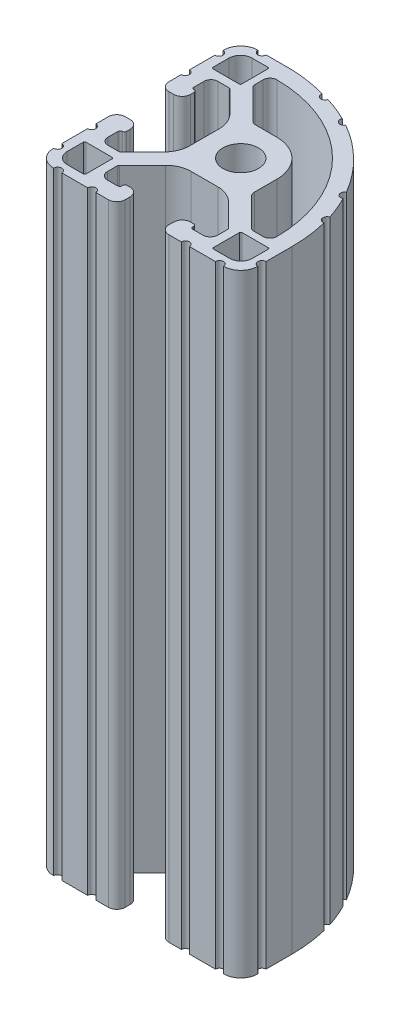
SolidWorks part; units mm, degrees
material "6061-T6 (SS)"
ref_plane "Front" through (0, 0, 0) normal (0, 0, 1) x (1, 0, 0)
ref_plane "Top" through (0, 0, 0) normal (0, 1, 0) x (1, 0, 0)
ref_plane "Right" through (0, 0, 0) normal (1, 0, 0) x (0, 0, -1)
sketch "Sketch1" plane through (0, 0, 0) normal (0, 0, 1) x (1, 0, 0)
  line L0 (0, -57.15) -> (0, 57.15)
  dimension "D1" = 114.3
other "15 1517 PROFILE(1)"
ref_plane "Plane1" through (0, -57.15, 0) normal (0, 1, 0) x (-1, 0, 0)
sketch "Sketch12" plane through (0, -57.15, 0) normal (0, 1, 0) x (-1, 0, 0)
  line L0 (0, 18.8774) -> (0, -24.5416) construction
  line L1 (24.2679, 0) -> (-24.0338, 0) construction
  line L3 (19.05, -19.05) -> (-19.05, -19.05) construction
  line L4 (11.8872, 16.9672) -> (11.8872, 12.0941)
  line L5 (12.1412, 11.8401) -> (17.018, 11.8401)
  line L6 (17.272, 12.0941) -> (17.272, 15.0876)
  line L7 (15.1384, 17.2212) -> (12.1412, 17.2212)
  line L8 (19.05, -19.05) -> (19.05, 19.05) construction
  line L9 (19.05, 19.05) -> (-19.05, 19.05) construction
  line L10 (-19.05, -19.05) -> (-19.05, 19.05) construction
  line L11 (19.05, -19.05) -> (-19.05, 19.05) construction
  line L12 (11.8923, -12.0941) -> (11.8923, -16.9672)
  line L13 (12.1463, -17.2212) -> (15.1384, -17.2212)
  line L14 (17.272, -15.0876) -> (17.272, -12.0941)
  line L15 (17.018, -11.8401) -> (12.1463, -11.8401)
  line L16 (19.05, 19.05) -> (-19.05, -19.05) construction
  line L22 (10.5713, -14.7676) -> (10.5713, -13.2314)
  line L23 (10.311, -12.6027) -> (4.8366, -7.1284)
  line L24 (3.9386, -6.7564) -> (0, -6.7564)
  line L25 (-6.7564, 0) -> (-6.7564, 4.2116)
  line L26 (-7.1284, 5.1096) -> (-12.3263, 10.3075)
  line L27 (-12.9549, 10.5679) -> (-14.7642, 10.5679)
  line L32 (-17.272, 15.0876) -> (-17.272, 12.1412)
  line L33 (-12.1412, 17.2212) -> (-15.1384, 17.2212)
  line L34 (-11.8872, 12.1412) -> (-11.8872, 16.9672)
  line L35 (-17.018, 11.8872) -> (-12.1412, 11.8872)
  line L78 (-5.8558, 8.1476) -> (-10.1754, 12.4672)
  line L79 (-10.287, 12.7366) -> (-10.287, 14.5699)
  line L80 (-8.8932, 15.9637) -> (-6.9992, 15.9637)
  line L81 (-6.6182, 15.5827) -> (-6.6182, 15.367)
  line L82 (-6.2372, 14.986) -> (-5.6388, 14.986)
  line L83 (-4.064, 16.5608) -> (-4.064, 17.4752)
  line L84 (-5.6388, 19.05) -> (-7.9758, 19.05)
  line L85 (-9.4998, 19.05) -> (-14.3282, 19.05)
  line L86 (-15.8522, 19.05) -> (-15.8759, 19.05)
  line L87 (-19.0509, 15.8761) -> (-19.0508, 15.8506)
  line L88 (-19.05, 14.3266) -> (-19.05, 12.7323)
  line L89 (-19.05, 12.7323) -> (-19.05, 9.525)
  line L90 (9.5111, -19.05) -> (12.7183, -19.05)
  line L91 (12.7183, -19.05) -> (14.3136, -19.05)
  line L92 (19.05, -14.2127) -> (19.05, -9.4945)
  line L93 (19.05, -7.9705) -> (19.05, -5.6388)
  line L94 (17.4752, -4.064) -> (16.5608, -4.064)
  line L95 (14.986, -5.6388) -> (14.986, -6.3233)
  line L96 (15.367, -6.7043) -> (15.4588, -6.7043)
  line L97 (15.8398, -7.0853) -> (15.8398, -9.017)
  line L98 (14.5698, -10.287) -> (12.4636, -10.287)
  line L99 (12.1942, -10.1754) -> (8.1486, -6.1298)
  line L100 (6.7564, -2.7688) -> (6.7564, 2.7688)
  line L101 (8.1486, 6.1298) -> (12.1942, 10.1754)
  line L102 (12.4636, 10.287) -> (14.5036, 10.287)
  line L103 (15.7736, 9.017) -> (15.7736, 7.0853)
  line L104 (15.3926, 6.7043) -> (15.367, 6.7043)
  line L105 (14.986, 6.3233) -> (14.986, 5.6388)
  line L106 (16.5608, 4.064) -> (17.4752, 4.064)
  line L107 (19.05, 5.6388) -> (19.05, 7.9759)
  line L108 (19.05, 9.4999) -> (19.05, 14.3284)
  line L109 (19.05, 15.8524) -> (19.05, 15.875)
  line L110 (15.875, 19.05) -> (15.847, 19.05)
  line L111 (14.323, 19.05) -> (9.4946, 19.05)
  line L112 (7.9706, 19.05) -> (5.6388, 19.05)
  line L113 (4.064, 17.4752) -> (4.064, 16.5608)
  line L114 (5.6388, 14.986) -> (6.2372, 14.986)
  line L115 (6.6182, 15.367) -> (6.6182, 15.5827)
  line L116 (6.9992, 15.9637) -> (8.8932, 15.9637)
  line L117 (10.287, 14.5699) -> (10.287, 12.7366)
  line L118 (10.1754, 12.4672) -> (5.8558, 8.1476)
  line L119 (2.4972, 6.7564) -> (-2.4972, 6.7564)
  arc A4 (12.1412, 17.2212) -> (11.8872, 16.9672) centre (12.1412, 16.9672) ccw
  arc A5 (11.8872, 12.0941) -> (12.1412, 11.8401) centre (12.1412, 12.0941) ccw
  arc A6 (17.018, 11.8401) -> (17.272, 12.0941) centre (17.018, 12.0941) ccw
  arc A7 (17.272, 15.0876) -> (15.1384, 17.2212) centre (15.1384, 15.0876) ccw
  arc A12 (11.8923, -16.9672) -> (12.1463, -17.2212) centre (12.1463, -16.9672) ccw
  arc A13 (15.1384, -17.2212) -> (17.272, -15.0876) centre (15.1384, -15.0876) ccw
  arc A14 (17.272, -12.0941) -> (17.018, -11.8401) centre (17.018, -12.0941) ccw
  arc A15 (12.1463, -11.8401) -> (11.8923, -12.0941) centre (12.1463, -12.0941) ccw
  arc A25 (9.269, -16.0372) -> (10.5713, -14.7676) centre (9.3013, -14.7676) ccw
  arc A26 (10.5713, -13.2314) -> (10.311, -12.6027) centre (9.6823, -13.2314) ccw
  arc A27 (4.8366, -7.1284) -> (3.9386, -6.7564) centre (3.9386, -8.0264) ccw
  arc A28 (-6.7564, 0) -> (0, -6.7564) centre (0, 0) ccw
  arc A29 (-6.7564, 4.2116) -> (-7.1284, 5.1096) centre (-8.0264, 4.2116) ccw
  arc A30 (-12.3263, 10.3075) -> (-12.9549, 10.5679) centre (-12.9549, 9.6789) ccw
  arc A31 (-14.7642, 10.5679) -> (-16.0341, 9.2879) centre (-14.7642, 9.2979) ccw
  arc A32 (-16.0341, 9.2879) -> (9.269, -16.0372) centre (9.4921, 9.4888) ccw
  circle A35 centre (0, 0) radius 3.3274
  arc A40 (-17.272, 12.1412) -> (-17.018, 11.8872) centre (-17.018, 12.1412) ccw
  arc A41 (-15.1384, 17.2212) -> (-17.272, 15.0876) centre (-15.1384, 15.0876) ccw
  arc A42 (-11.8872, 16.9672) -> (-12.1412, 17.2212) centre (-12.1412, 16.9672) ccw
  arc A43 (-12.1412, 11.8872) -> (-11.8872, 12.1412) centre (-12.1412, 12.1412) ccw
  arc A95 (-10.287, 12.7366) -> (-10.1754, 12.4672) centre (-9.906, 12.7366) ccw
  arc A96 (-8.8932, 15.9637) -> (-10.287, 14.5699) centre (-8.8932, 14.5699) ccw
  arc A97 (-6.6182, 15.5827) -> (-6.9992, 15.9637) centre (-6.9992, 15.5827) ccw
  arc A98 (-6.6182, 15.367) -> (-6.2372, 14.986) centre (-6.2372, 15.367) ccw
  arc A99 (-5.6388, 14.986) -> (-4.064, 16.5608) centre (-5.6388, 16.5608) ccw
  arc A100 (-4.064, 17.4752) -> (-5.6388, 19.05) centre (-5.6388, 17.4752) ccw
  arc A101 (-9.4998, 19.05) -> (-7.9758, 19.05) centre (-8.7378, 19.05) ccw
  arc A102 (-15.8522, 19.05) -> (-14.3282, 19.05) centre (-15.0902, 19.05) ccw
  arc A103 (-15.8759, 19.05) -> (-19.0509, 15.8761) centre (-15.8759, 15.875) ccw
  arc A104 (-19.05, 14.3266) -> (-19.0508, 15.8506) centre (-19.0504, 15.0886) ccw
  arc A105 (-19.05, 9.525) -> (-18.2241, 2.6723) centre (9.4921, 9.4888) ccw
  arc A106 (-17.8208, 1.2027) -> (-18.2241, 2.6723) centre (-18.0323, 1.9348) ccw
  arc A107 (-17.8208, 1.2027) -> (-16.0569, -3.0251) centre (9.3479, 10.0565) ccw
  arc A108 (-15.3417, -4.3707) -> (-16.0569, -3.0251) centre (-15.7082, -3.7026) ccw
  arc A109 (-15.3417, -4.3707) -> (-10.5738, -10.4703) centre (9.348, 10.0152) ccw
  arc A110 (-10.5738, -10.4703) -> (-4.4477, -15.1275) centre (9.6252, 9.7419) ccw
  arc A111 (-3.1021, -15.8427) -> (-4.4477, -15.1275) centre (-3.7797, -15.4941) ccw
  arc A112 (-3.1021, -15.8427) -> (1.3376, -17.6058) centre (9.6276, 9.7402) ccw
  arc A113 (2.8072, -18.0091) -> (1.3376, -17.6058) centre (2.0697, -17.8173) ccw
  arc A114 (2.8072, -18.0091) -> (9.5111, -19.05) centre (10.5124, 9.5075) ccw
  arc A115 (15.8376, -19.0507) -> (14.3136, -19.05) centre (15.0756, -19.0504) ccw
  arc A116 (15.8376, -19.0507) -> (19.05, -15.7367) centre (15.8781, -15.876) ccw
  arc A117 (19.05, -14.2127) -> (19.05, -15.7367) centre (19.05, -14.9747) ccw
  arc A118 (19.05, -7.9705) -> (19.05, -9.4945) centre (19.05, -8.7325) ccw
  arc A119 (19.05, -5.6388) -> (17.4752, -4.064) centre (17.4752, -5.6388) ccw
  arc A120 (16.5608, -4.064) -> (14.986, -5.6388) centre (16.5608, -5.6388) ccw
  arc A121 (14.986, -6.3233) -> (15.367, -6.7043) centre (15.367, -6.3233) ccw
  arc A122 (15.8398, -7.0853) -> (15.4588, -6.7043) centre (15.4588, -7.0853) ccw
  arc A123 (14.5698, -10.287) -> (15.8398, -9.017) centre (14.5698, -9.017) ccw
  arc A124 (12.1942, -10.1754) -> (12.4636, -10.287) centre (12.4636, -9.906) ccw
  arc A125 (6.7564, -2.7688) -> (8.1486, -6.1298) centre (11.5096, -2.7688) ccw
  arc A126 (8.1486, 6.1298) -> (6.7564, 2.7688) centre (11.5096, 2.7688) ccw
  arc A127 (12.4636, 10.287) -> (12.1942, 10.1754) centre (12.4636, 9.906) ccw
  arc A128 (15.7736, 9.017) -> (14.5036, 10.287) centre (14.5036, 9.017) ccw
  arc A129 (15.3926, 6.7043) -> (15.7736, 7.0853) centre (15.3926, 7.0853) ccw
  arc A130 (15.367, 6.7043) -> (14.986, 6.3233) centre (15.367, 6.3233) ccw
  arc A131 (14.986, 5.6388) -> (16.5608, 4.064) centre (16.5608, 5.6388) ccw
  arc A132 (17.4752, 4.064) -> (19.05, 5.6388) centre (17.4752, 5.6388) ccw
  arc A133 (19.05, 9.4999) -> (19.05, 7.9759) centre (19.05, 8.7379) ccw
  arc A134 (19.05, 15.8524) -> (19.05, 14.3284) centre (19.05, 15.0904) ccw
  arc A135 (19.05, 15.875) -> (15.875, 19.05) centre (15.875, 15.875) ccw
  arc A136 (14.323, 19.05) -> (15.847, 19.05) centre (15.085, 19.05) ccw
  arc A137 (7.9706, 19.05) -> (9.4946, 19.05) centre (8.7326, 19.05) ccw
  arc A138 (5.6388, 19.05) -> (4.064, 17.4752) centre (5.6388, 17.4752) ccw
  arc A139 (4.064, 16.5608) -> (5.6388, 14.986) centre (5.6388, 16.5608) ccw
  arc A140 (6.2372, 14.986) -> (6.6182, 15.367) centre (6.2372, 15.367) ccw
  arc A141 (6.9992, 15.9637) -> (6.6182, 15.5827) centre (6.9992, 15.5827) ccw
  arc A142 (10.287, 14.5699) -> (8.8932, 15.9637) centre (8.8932, 14.5699) ccw
  arc A143 (10.1754, 12.4672) -> (10.287, 12.7366) centre (9.906, 12.7366) ccw
  arc A144 (2.4972, 6.7564) -> (5.8558, 8.1476) centre (2.4972, 11.5062) ccw
  arc A145 (-5.8558, 8.1476) -> (-2.4972, 6.7564) centre (-2.4972, 11.5062) ccw
  point P76 (0, 19.05)
  point P207 (0, -19.05)
  point P208 (-19.05, 19.05)
  point P209 (19.05, -19.05)
  point P210 (0, 0)
  point P211 (-19.05, 0)
  point P212 (19.05, 0)
  point P213 (-19.05, -19.05)
  point P214 (19.05, 19.05)
  point P215 (0, 0)
  dimension "D1" = 6.6548
  dimension "D2" = 8.128
  dimension "D3" = 38.1
  dimension "D9" = 28.575
  dimension "D4" = 19.05
  dimension "D5" = 12.2936
  dimension "D6" = 4.064
  dimension "D7" = 20.574
  dimension "D8" = 3.9624
  dimension "D10" = 3.048
  dimension "D11" = 1.6002
  dimension "D12" = 5.3848
  dimension "D13" = 1.8288
